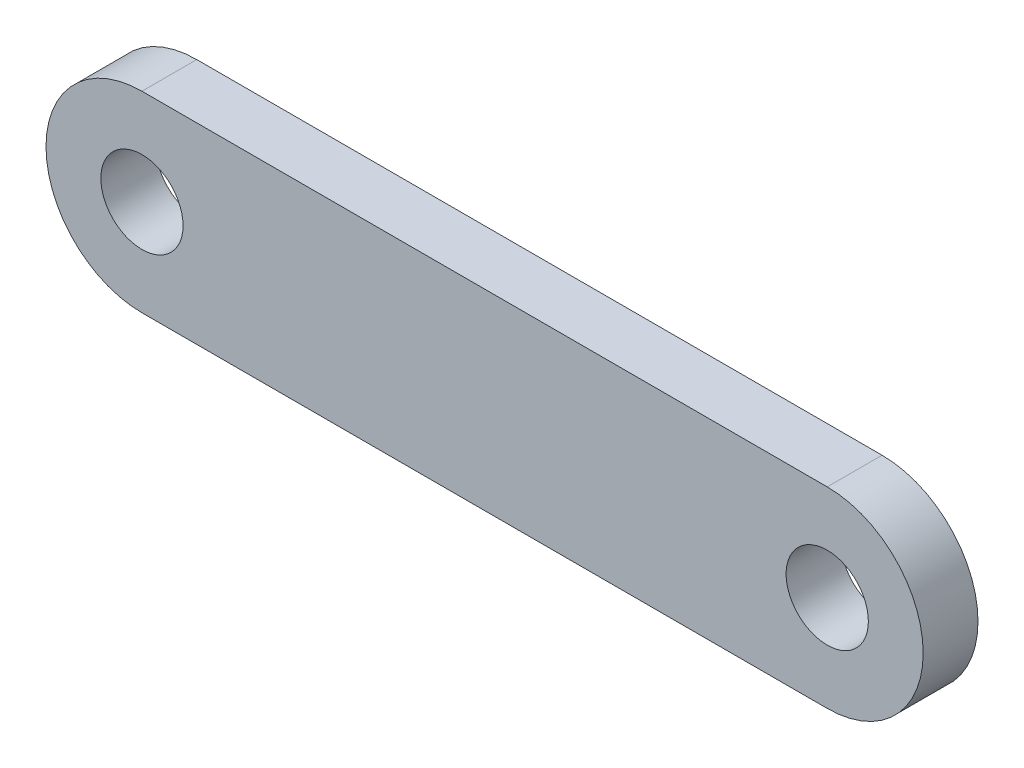
SolidWorks part; units mm, degrees
material "Thornel Mat VMA"
ref_plane "前视基准面" through (0, 0, 0) normal (0, 0, 1) x (1, 0, 0)
ref_plane "上视基准面" through (0, 0, 0) normal (0, 1, 0) x (1, 0, 0)
ref_plane "右视基准面" through (0, 0, 0) normal (1, 0, 0) x (0, 0, -1)
sketch "草图1" plane through (0, 0, 0) normal (0, 0, 1) x (1, 0, 0)
  line L0 (-12.5, 0) -> (12.5, 0) construction
  line L1 (-12.5, 3.5) -> (12.5, 3.5)
  line L2 (-12.5, -3.5) -> (12.5, -3.5)
  arc A0 (-12.5, 3.5) -> (-12.5, -3.5) centre (-12.5, 0) ccw
  arc A1 (12.5, -3.5) -> (12.5, 3.5) centre (12.5, 0) ccw
  circle A2 centre (12.5, 0) radius 1.5
  circle A3 centre (-12.5, 0) radius 1.5
  point P2 (0, 0)
  dimension "D2" = 3
  dimension "D3" = 2
  dimension "D1" = 25
extrude "凸台-拉伸1" add sketch "草图1" along normal mid plane 2
